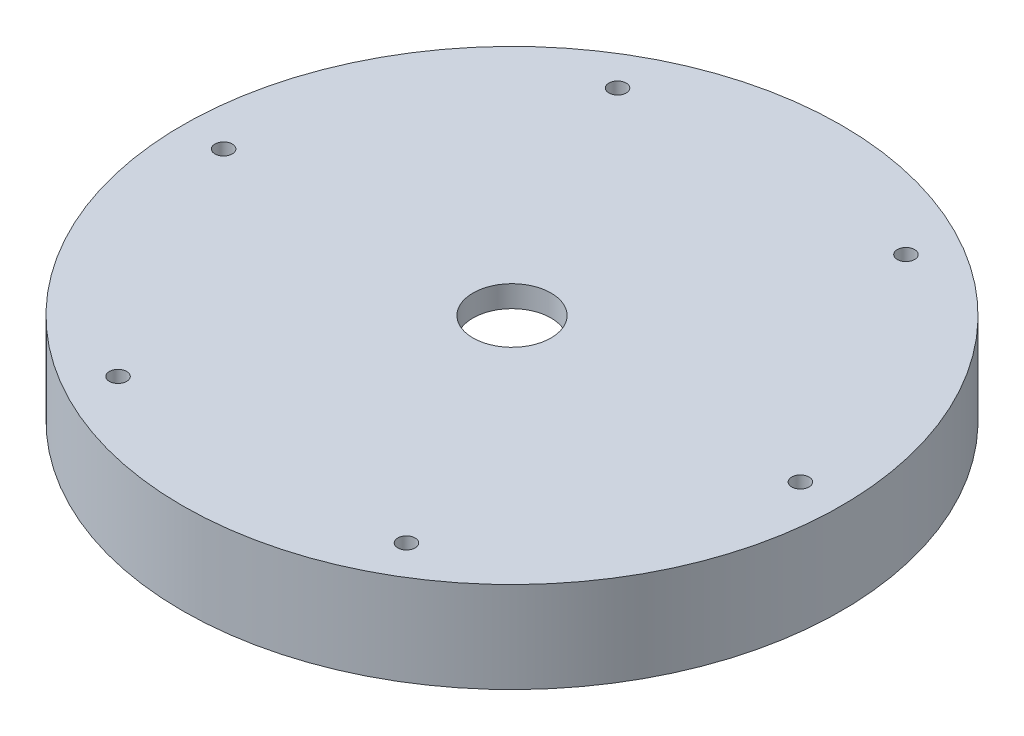
SolidWorks part; units mm, degrees
material "1060 Alloy"
ref_plane "Front Plane" through (0, 0, 0) normal (0, 0, 1) x (1, 0, 0)
ref_plane "Top Plane" through (0, 0, 0) normal (0, 1, 0) x (1, 0, 0)
ref_plane "Right Plane" through (0, 0, 0) normal (1, 0, 0) x (0, 0, -1)
sketch "Sketch1" plane through (0, 0, 0) normal (0, 0, 1) x (1, 0, 0)
  line L0 (0, 38.7087) -> (0, -19.5852) construction
  line L1 (-4.5, 0) -> (-38.0375, 0)
  line L2 (-38.0375, 0) -> (-38.0375, -10.5)
  line L4 (-20, -11.75) -> (-20, -2.5)
  line L5 (-20, -2.5) -> (-4.5, -2.5)
  line L6 (-4.5, -2.5) -> (-4.5, 0)
  line L7 (-20, -11.75) -> (-35.0375, -11.75)
  line L8 (-35.0375, -11.75) -> (-35.0375, -10.5)
  line L9 (-35.0375, -10.5) -> (-38.0375, -10.5)
  dimension "D1" = 4.5
  dimension "D2" = 20
  dimension "D4" = 38.0375
  dimension "D5" = 3
  dimension "D6" = 1.25
  dimension "D7" = 2.5
  dimension "D3" = 8
revolve "Revolve1" add sketch "Sketch1" angle 360 about L0
sketch "Sketch2" plane through (0, -11.75, 0) normal (0, -1, 0) x (1, 0, 0)
  circle A0 centre (0, 0) radius 33.2875 construction
  circle A1 centre (-33.2875, 0) radius 1
  circle A2 centre (-16.6438, 28.8278) radius 1
  circle A3 centre (16.6437, 28.8278) radius 1
  circle A4 centre (33.2875, 0) radius 1
  circle A5 centre (16.6438, -28.8278) radius 1
  circle A6 centre (-16.6437, -28.8278) radius 1
  point P17 (0, 0)
  dimension "D1" = 2
  dimension "D3" = 66.575
  dimension "D2" = 6
extrude "Cut-Extrude1" cut sketch "Sketch2" against normal through all
equation "\"Stator_OD\"= 60'No Tolerance given"
equation "\"A\"=35.81 'taken off spec sheet for 06808 (A)"
equation "\"Rotor_ID\"= 30'No Tolerance Given"
equation "\"back_bearing_Thickness\"= 8'randomish, thinnest off mcmaster"
equation "\"back_bearing_OD\"= 25'currently non-sense"
equation "\"Stator_Gap\"= 0.0375'+- 0.0125 (From 1.3.3.1 Kollmorgen manual)"
equation "\"Back_mount_hole\"= 1.75'To be tapped to M2 (USE LOCKTITE)"
equation "\"facePlate_Mount_Hole\"= 5.75'To be tapped to M6"
equation "\"back_bearing_ID\"= 15'Random number"
equation "\"final_shaftD\"= 8'NEMA 23 shaft diameter. Should fit with harmonic?"
equation "\"final_shaftL\"= 50'random length. Idk"
equation "\"back_bearing_IDOD\"= 18'Random number, OD of the inner bearing ring"
equation "\"rotor_shaftD\"= \"Rotor_ID\" - (\"rotor-shaft_gap\")*2'"
equation "\"front_bearing_ID\"= 12'random"
equation "\"front_bearing_OD\"= 20'random"
equation "\"front_bearing_IDOD\"= 14'random"
equation "\"front_bearing_Thickness\"= 5'randomish, thinnest off mcmaster"
equation "\"rotor_thickness\"= 2.4'measured off CAD"
equation "\"rotor_height\"= 32.86'+-0.075 taken off spec sheet for 06826 (C)"
equation "\"D1@Sketch1\"=\"final_shaftD\"/2+0.5"
equation "\"D2@Sketch1\"=\"front_bearing_OD\""
equation "\"D4@Sketch1\"=\"Stator_OD\"/2+\"Stator_Gap\"+8"
equation "\"D3@Sketch1\"=\"front_bearing_Thickness\"+3"
equation "\"D3@Sketch2\"= \"Stator_OD\" + \"Stator_Gap\" * 2 + 6.5"
equation "\"D1@Sketch2\"=\"Back_mount_hole\"+0.25"
